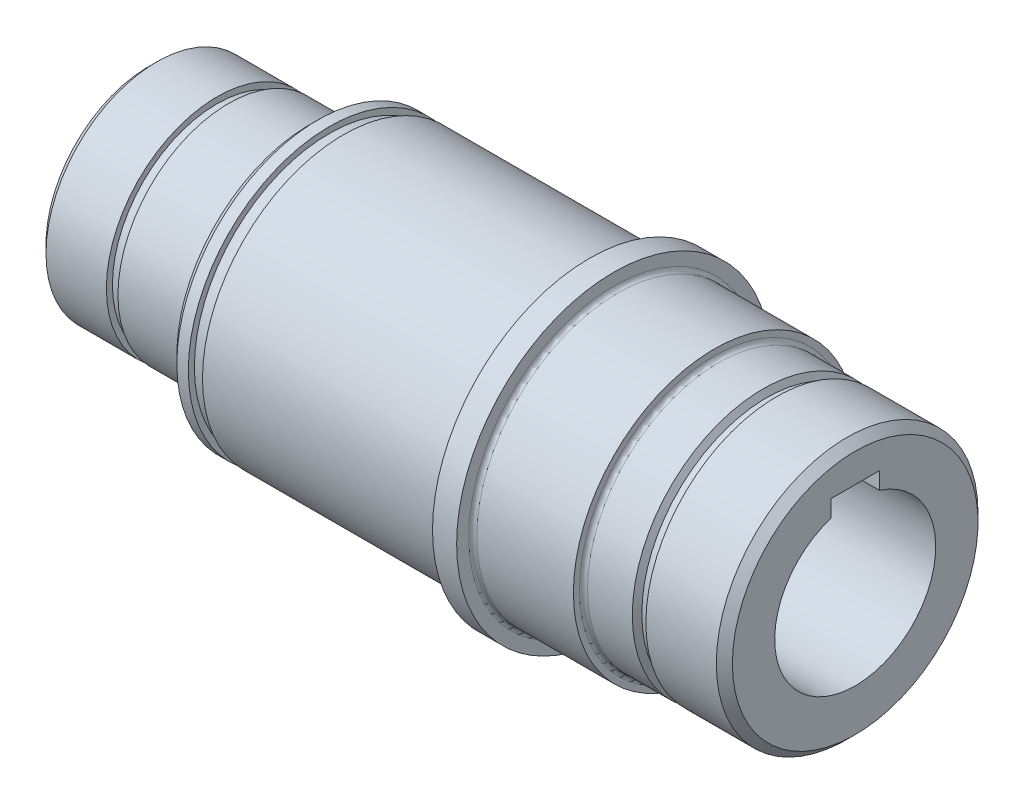
SolidWorks part; units mm, degrees
ref_plane "Piano frontale" through (0, 0, 0) normal (0, 0, 1) x (1, 0, 0)
ref_plane "Piano superiore" through (0, 0, 0) normal (0, 1, 0) x (1, 0, 0)
ref_plane "Piano destro" through (0, 0, 0) normal (1, 0, 0) x (0, 0, -1)
sketch "Schizzo1" plane through (0, 0, 0) normal (0, 0, 1) x (1, 0, 0)
  line L0 (0, 0) -> (0, 27.5)
  line L2 (40, 27.5) -> (40, 35)
  line L4 (109.5, 35) -> (109.5, 39)
  line L8 (175.5, 32.5) -> (175.5, 0)
  line L9 (0, 0) -> (175.5, 0) construction
  line L10 (0, 0) -> (175.5, 0)
  line L23 (109.5, 35) -> (40, 35)
  line L24 (109.5, 39) -> (115.5, 39)
  line L25 (115.5, 39) -> (115.5, 35)
  line L26 (115.5, 35) -> (140.5, 35)
  line L27 (140.5, 35) -> (140.5, 32.5)
  line L28 (140.5, 32.5) -> (152.634, 32.5)
  line L31 (156, 31) -> (156, 32.5)
  line L32 (156, 32.5) -> (175.5, 32.5)
  line L33 (152.634, 32.5) -> (153.5, 31)
  line L34 (153.5, 31) -> (156, 31)
  line L35 (40, 27.5) -> (19.866, 27.5)
  line L36 (19.866, 27.5) -> (19, 26)
  line L37 (19, 26) -> (17, 26)
  line L38 (17, 26) -> (17, 27.5)
  line L39 (17, 27.5) -> (0, 27.5)
  dimension "D1" = 27.5
  dimension "D2" = 40
  dimension "D3" = 35
  dimension "D4" = 69.5
  dimension "D5" = 60
  dimension "D6" = 6
  dimension "D7" = 35
  dimension "D8" = 175.5
  dimension "D9" = 39
  dimension "D10" = 35
  dimension "D11" = 2.5
  dimension "D12" = 13
  dimension "D13" = 32.5
  dimension "D14" = 32.5
  dimension "D15" = 31
  dimension "D16" = 90
  dimension "D17" = 60
  dimension "D18" = 26
  dimension "D19" = 21
  dimension "D20" = 2
  dimension "D21" = 27.5
revolve "Rivoluzione1" add sketch "Schizzo1" angle 360 about L9
sketch "Schizzo2" plane through (0, 0, 0) normal (-1, 0, 0) x (0, 0, 1)
  line L0 (0, 20) -> (0, 23.3) construction
  line L1 (-6, 23.3) -> (6, 23.3)
  line L2 (-6, 23.3) -> (-6, 19.0788)
  line L3 (6, 23.3) -> (6, 19.0788)
  circle A0 centre (0, 0) radius 20
  point P7 (0, 23.3)
  dimension "D1" = 40
  dimension "D2" = 3.3
  dimension "12" = 12
extrude "Taglio-Estrusione1" cut sketch "Schizzo2" against normal through all contours A0 L0 L1 L2 | L0 A0 L3 L1 | A0
chamfer "Smusso1" distance 2 angle 45 3 edges at (175.5, 0, 32.5) (40, 0, 35) (0, 0, 27.5)
fillet "Raccordo1" radius 1 3 edges at (115.5, 0, 35) (140.5, 0, 32.5) (109.5, 0, 35)
sketch "Schizzo3" plane through (0, 0, 0) normal (0, 0, 1) x (1, 0, 0)
  line L0 (48.366, 35) -> (47.5, 33.5)
  line L1 (108.5, 35) -> (42, 35) construction
  line L2 (47.5, 33.5) -> (44.85, 33.5)
  line L3 (44.85, 33.5) -> (44.85, 35)
  line L4 (44.85, 35) -> (48.366, 35)
  line L5 (-16.4122, 0) -> (83.044, 0) construction
  line L6 (109.5, 39) -> (109.5, -39) construction
  dimension "D1" = 120
  dimension "D2" = 1.5
  dimension "D3" = 2.65
  dimension "D4" = 62
revolve "Taglia-Rivoluzione1" cut sketch "Schizzo3" angle 360 about L5
sketch "Schizzo4" plane through (0, 0, 0) normal (0, 1, 0) x (1, 0, 0)
  line L0 (60.5, 0) -> (96.5, 0) construction
  line L1 (60.5, 10) -> (96.5, 10)
  line L2 (60.5, -10) -> (96.5, -10)
  line L3 (109.5, 36) -> (109.5, -36) construction
  arc A0 (60.5, 10) -> (60.5, -10) centre (60.5, 0) ccw
  arc A1 (96.5, -10) -> (96.5, 10) centre (96.5, 0) ccw
  point P3 (78.5, 0)
  dimension "D1" = 20
  dimension "D2" = 36
  dimension "D3" = 13
extrude "Taglio-Estrusione2" cut sketch "Schizzo4" along normal blind 5 from offset 35 offset against normal yes
